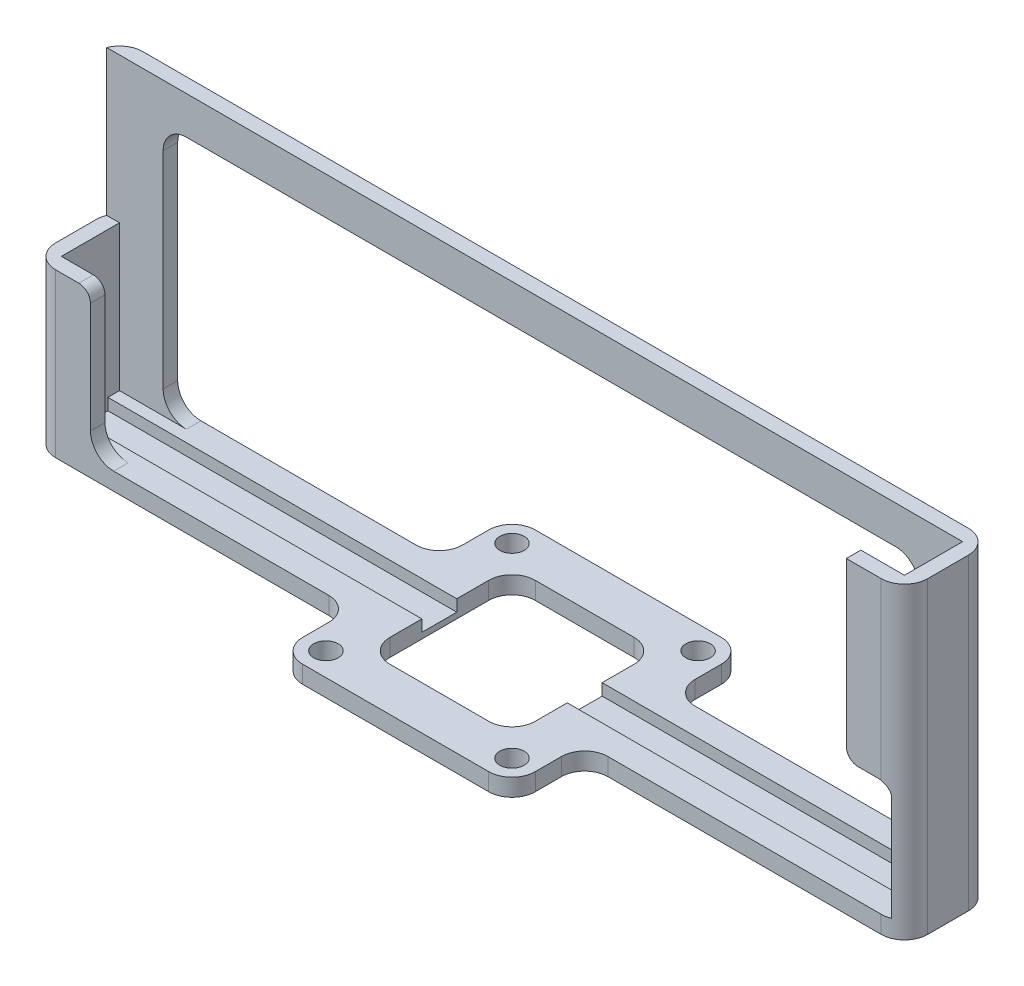
SolidWorks part; units mm, degrees
ref_plane "Front" through (0, 0, 0) normal (0, 0, 1) x (1, 0, 0)
ref_plane "Top" through (0, 0, 0) normal (0, 1, 0) x (1, 0, 0)
ref_plane "Right" through (0, 0, 0) normal (1, 0, 0) x (0, 0, -1)
sketch "Sketch1" plane through (0, 0, 0) normal (0, 1, 0) x (1, 0, 0)
  line L0 (-65, 5) -> (-65, 7.5)
  line L1 (-72.5, -5) -> (-65, -5)
  line L2 (-72.5, -5) -> (-72.5, 5)
  line L3 (-72.5, 5) -> (-65, 5)
  line L4 (72.5, -5) -> (72.5, 5)
  line L5 (65, 5) -> (65, 7.5)
  line L7 (-75, 7.5) -> (-65, 7.5)
  line L8 (-75, 7.5) -> (-75, -7.5)
  line L9 (-75, -7.5) -> (-65, -7.5)
  line L10 (75, 7.5) -> (75, -7.5)
  line L13 (-65, -7.5) -> (-65, -5)
  line L15 (65, -7.5) -> (65, -5)
  line L16 (65, -7.5) -> (75, -7.5)
  line L18 (65, -5) -> (72.5, -5)
  line L22 (65, 5) -> (72.5, 5)
  line L23 (65, 7.5) -> (75, 7.5)
  point P0 (0, 0)
  point P5 (0, 0)
extrude "Boss-Extrude1" add sketch "Sketch1" along normal blind 50
sketch "Sketch2" plane through (0, 0, -7.5) normal (0, 0, -1) x (-1, 0, 0)
  line L0 (-65, 50) -> (65, 50)
  line L1 (65, 50) -> (65, 43.4958)
  line L2 (65, 50) -> (65, 0) construction
  line L3 (65, 43.4958) -> (-65, 43.4958)
  line L4 (-65, 50) -> (-65, 0) construction
  line L5 (-65, 43.4958) -> (-65, 50)
extrude "Boss-Extrude2" add sketch "Sketch2" against normal blind 2.5
sketch "Sketch4" plane through (0, 0, 0) normal (0, -1, 0) x (1, 0, 0)
  line L0 (20, 7.5) -> (75, 7.5)
  line L3 (-75, -7.5) -> (-20, -7.5)
  line L4 (75, 7.5) -> (75, -7.5)
  line L9 (-16, -16) -> (16.0011, 16.0011) construction
  line L10 (-16, 16) -> (16, -16) construction
  line L11 (-20, -20) -> (20, -20)
  line L12 (-20, -20) -> (-20, -7.5)
  line L13 (-20, 20) -> (20, 20)
  line L14 (20, -20) -> (20, -7.5)
  line L15 (-20, -20) -> (20, 20) construction
  line L16 (-20, 20) -> (20, -20) construction
  line L17 (-20, 7.5) -> (-20, 20)
  line L18 (20, 7.5) -> (20, 20)
  line L19 (20, -7.5) -> (75, -7.5)
  line L21 (-75, -7.5) -> (-75, 7.5)
  line L22 (-75, 7.5) -> (-20, 7.5)
  line L24 (-12.4995, -12.4995) -> (12.5005, -12.4995)
  line L25 (-12.4995, -12.4995) -> (-12.4995, 12.5005)
  line L26 (-12.4995, 12.5005) -> (12.5005, 12.5005)
  line L27 (12.5005, -12.4995) -> (12.5005, 12.5005)
  line L28 (-12.4995, -12.4995) -> (12.5005, 12.5005) construction
  line L29 (-12.4995, 12.5005) -> (12.5005, -12.4995) construction
  circle A0 centre (16.0011, 16.0011) radius 2.1
  circle A1 centre (-16, 16) radius 2.1
  circle A2 centre (-16, -16) radius 2.1
  circle A3 centre (16, -16) radius 2.1
  point P4 (0, 0)
  point P11 (0, 0)
  point P25 (0.0005, 0.0005)
extrude "Boss-Extrude4" add sketch "Sketch4" along normal blind 3
fillet "Fillet1" radius 4 22 edges at (75, 23.5, 7.5) (75, 23.5, -7.5) (-75, 23.5, -7.5) (-65, 43.4958, -6.25) (65, 43.4958, -6.25) (65, 0, 6.25) (65, 0, -6.25) (-65, 0, 6.25) (-65, 0, -6.25) (-20, -1.5, 7.5) (20, -1.5, 20) (20, -1.5, 7.5) (20, -1.5, -7.5) (20, -1.5, -20) (-20, -1.5, -20) (-20, -1.5, -7.5) (-20, -1.5, 20) (-75, 23.5, 7.5) (-12.4995, -1.5, -12.4995) (12.5005, -1.5, -12.4995) (12.5005, -1.5, 12.5005) (-12.4995, -1.5, 12.5005)
sketch "Sketch5" plane through (0, 0, 0) normal (0, 1, 0) x (1, 0, 0)
  line L0 (72.5, 5) -> (72.5, -5) construction
  line L1 (-72.5, -3) -> (72.5, -3)
  line L2 (-72.5, -3) -> (-72.5, 3)
  line L3 (-72.5, 3) -> (72.5, 3)
  line L4 (72.5, -3) -> (72.5, 3)
  line L5 (-72.5, -3) -> (72.5, 3) construction
  line L6 (-72.5, 3) -> (72.5, -3) construction
  point P0 (0, 0)
extrude "Cut-Extrude1" cut sketch "Sketch5" against normal blind 2
sketch "Sketch6" plane through (-72.5, 0, 0) normal (1, 0, 0) x (0, 0, -1)
  line L0 (-14.5328, 51.3581) -> (-14.5328, 25)
  line L1 (-5, 25) -> (5, 25)
  line L2 (-5, 50) -> (-5, 0) construction
  line L3 (5, 50) -> (5, 0) construction
  line L4 (5, 25) -> (5, 51.3581)
  line L5 (5, 51.3581) -> (-14.5328, 51.3581)
  line L7 (-14.5328, 25) -> (-5, 25)
extrude "Cut-Extrude2" cut sketch "Sketch6" against normal blind 5
sketch "Sketch7" plane through (-72.5, 0, 0) normal (-1, 0, 0) x (0, 0, 1)
  line L0 (5, 50) -> (5, 0) construction
  line L1 (5, 25) -> (9.1528, 25)
  line L2 (5, 25) -> (5, 50.0889)
  line L3 (5, 50.0889) -> (9.1528, 50.0889)
  line L4 (9.1528, 25) -> (9.1528, 50.0889)
extrude "Cut-Extrude3" cut sketch "Sketch7" against normal blind 15
sketch "Sketch8" plane through (0, 0, 7.5) normal (0, 0, 1) x (1, 0, 0)
  line L5 (61, 0) -> (72.5, 0)
  line L6 (72.5, 0) -> (72.5, 20)
  line L7 (72.5, 20) -> (61, 20)
  line L8 (61, 20) -> (61, 0)
extrude "Cut-Extrude5" cut sketch "Sketch8" against normal blind 5
fillet "Fillet2" radius 2 3 edges at (72.5, 20, 6.104) (-65, 25, 6.25) (65, 20, 6.25)
